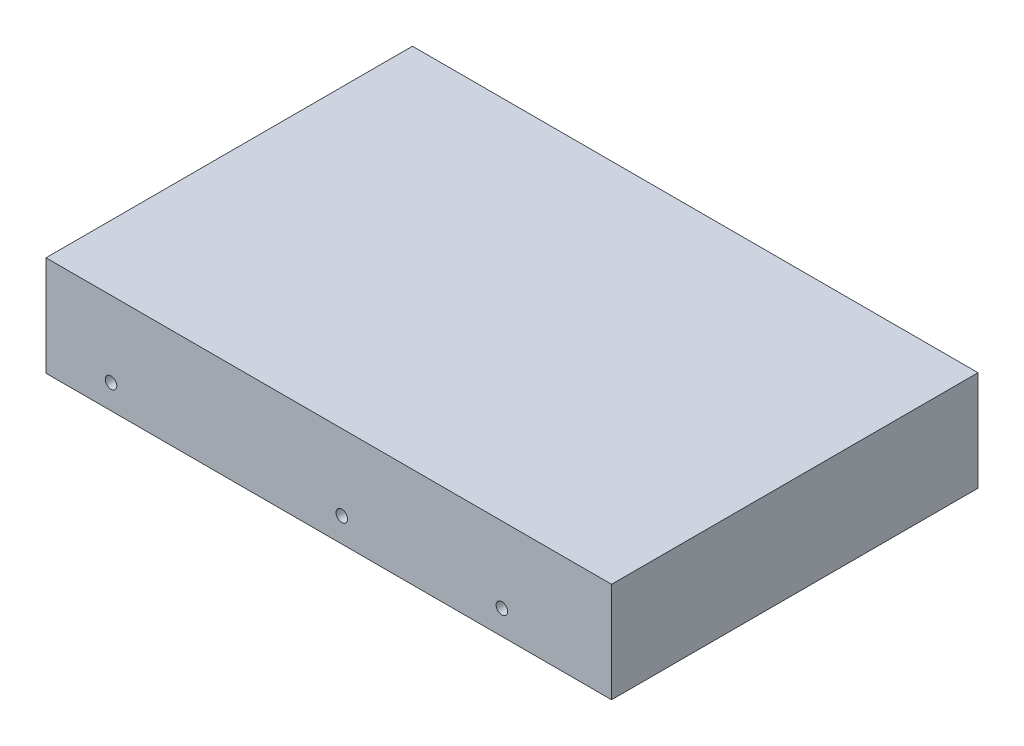
SolidWorks part; units mm, degrees
ref_plane "Front Plane" through (0, 0, 0) normal (0, 0, 1) x (1, 0, 0)
ref_plane "Top Plane" through (0, 0, 0) normal (0, 1, 0) x (1, 0, 0)
ref_plane "Right Plane" through (0, 0, 0) normal (1, 0, 0) x (0, 0, -1)
sketch "Sketch1" plane through (0, 0, 0) normal (0, 1, 0) x (1, 0, 0)
  line L1 (-65.3799, 55.8758) -> (81.6201, 55.8758)
  line L2 (-65.3799, 55.8758) -> (-65.3799, -39.3742)
  line L3 (-65.3799, -39.3742) -> (81.6201, -39.3742)
  line L4 (81.6201, 55.8758) -> (81.6201, -39.3742)
  dimension "D1" = 95.25
  dimension "D2" = 147
extrude "Boss-Extrude1" add sketch "Sketch1" along normal blind 26
sketch "Sketch2" plane through (0, 0, 39.3742) normal (0, 0, 1) x (1, 0, 0)
  line L0 (81.6201, 0) -> (53.1201, 0)
  line L1 (-65.3799, 0) -> (81.6201, 0) construction
  line L3 (53.1201, 0) -> (-48.4799, 0)
  line L4 (-48.4799, 0) -> (-48.4799, 6.35)
  line L5 (11.5101, 0) -> (11.5101, 6.35)
  line L6 (53.1201, 0) -> (53.1201, 6.35)
  circle A0 centre (-48.4799, 6.35) radius 1.5
  circle A1 centre (11.5101, 6.35) radius 1.5
  circle A2 centre (53.1201, 6.35) radius 1.5
  point P13 (0, 0)
  dimension "D4" = 6.35
  dimension "D7" = 3
  dimension "D8" = 3
  dimension "D9" = 3
  dimension "D1" = 28.5
  dimension "D2" = 41.61
  dimension "D3" = 101.6
  dimension "D5" = 6.35
  dimension "D6" = 6.35
extrude "Cut-Extrude3" cut sketch "Sketch2" against normal blind 26 contours A2 | A1 | A0
